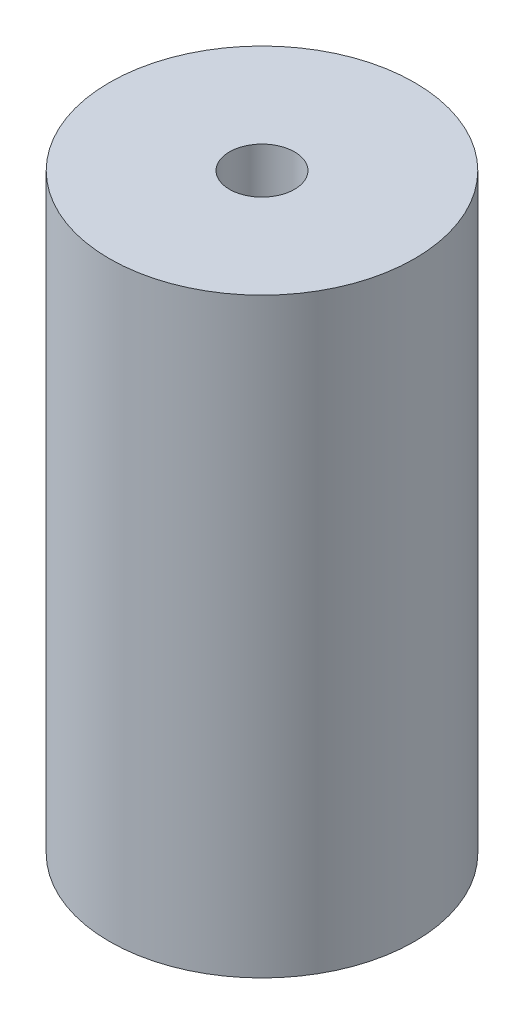
SolidWorks part; units mm, degrees
material "Rocket Candy"
ref_plane "Front Plane" through (0, 0, 0) normal (0, 0, 1) x (1, 0, 0)
ref_plane "Top Plane" through (0, 0, 0) normal (0, 1, 0) x (1, 0, 0)
ref_plane "Right Plane" through (0, 0, 0) normal (1, 0, 0) x (0, 0, -1)
sketch "Sketch1" plane through (0, 0, 0) normal (0, 1, 0) x (1, 0, 0)
  circle A0 centre (0, 0) radius 38.71
  circle A1 centre (0, 0) radius 8.25
  dimension "D1" = 77.42
  dimension "D2" = 16.5
extrude "Boss-Extrude1" add sketch "Sketch1" along normal blind 150
